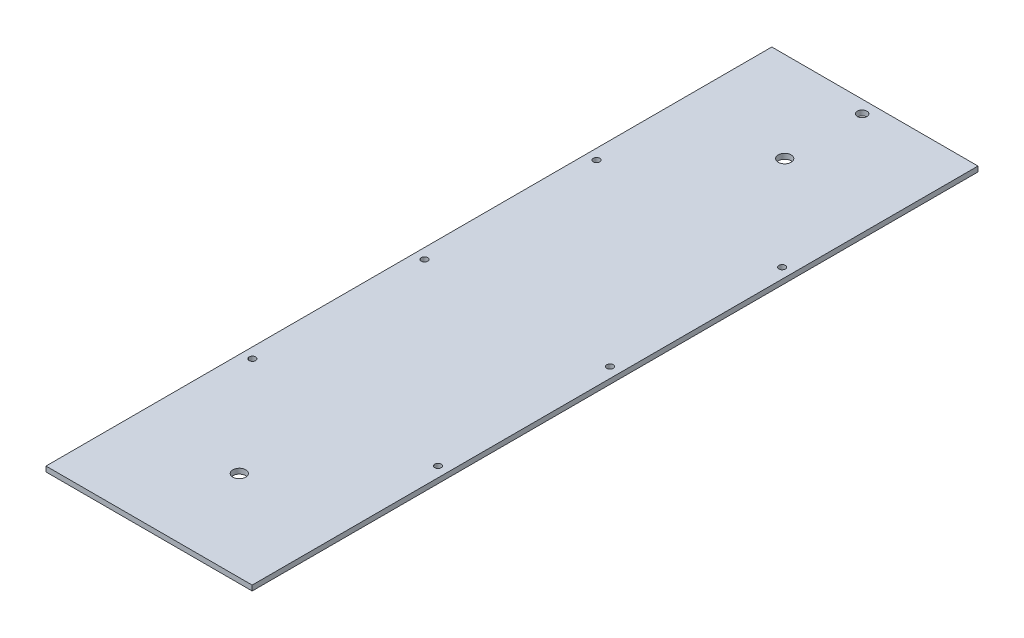
SolidWorks part; units mm, degrees
ref_plane "Front" through (0, 0, 0) normal (0, 0, 1) x (1, 0, 0)
ref_plane "Top" through (0, 0, 0) normal (0, 1, 0) x (1, 0, 0)
ref_plane "Right" through (0, 0, 0) normal (1, 0, 0) x (0, 0, -1)
sketch "Sketch1" plane through (0, 0, 0) normal (0, 1, 0) x (1, 0, 0)
  line L1 (-40, -140.81) -> (40, -140.81)
  line L2 (-40, -140.81) -> (-40, 140.81)
  line L3 (-40, 140.81) -> (40, 140.81)
  line L4 (40, -140.81) -> (40, 140.81)
  line L5 (-40, -140.81) -> (40, 140.81) construction
  line L6 (-40, 140.81) -> (40, -140.81) construction
  point P0 (0, 0)
  dimension "D1" = 281.62
  dimension "D2" = 80
extrude "Boss-Extrude1" add sketch "Sketch1" along normal blind 2
sketch "Sketch2" plane through (0, 2, 0) normal (0, 1, 0) x (1, 0, 0)
  line L0 (40, 140.81) -> (-40, 140.81) construction
  circle A0 centre (0, 135.87) radius 1.85
  dimension "D1" = 3.7
  dimension "D2" = 4.94
extrude "Cut-Extrude1" cut sketch "Sketch2" against normal blind 2
sketch "Sketch3" plane through (0, 2, 0) normal (0, 1, 0) x (1, 0, 0)
  line L0 (-40, 140.81) -> (-40, -140.81) construction
  line L1 (40, 140.81) -> (-40, 140.81) construction
  circle A0 centre (-36, 68.81) radius 1.25
  dimension "D1" = 2.5
  dimension "D2" = 4
  dimension "D3" = 72
extrude "Cut-Extrude2" cut sketch "Sketch3" against normal blind 2
pattern_linear "LPattern1" count 3 spacing 66.76 along (0, 0, 1) of "Cut-Extrude2"
mirror "Mirror1" about plane through (0, 0, 0) normal (1, 0, 0) of "LPattern1", "Cut-Extrude2"
sketch "Sketch4" plane through (0, 2, 0) normal (0, 1, 0) x (1, 0, 0)
  line L0 (40, 140.81) -> (-40, 140.81) construction
  circle A0 centre (0, 105.81) radius 2.5
  dimension "D1" = 5
  dimension "D2" = 35
extrude "Cut-Extrude3" cut sketch "Sketch4" against normal blind 10
mirror "Mirror2" about plane through (0, 0, 0) normal (0, 0, 1) of "Cut-Extrude3"
